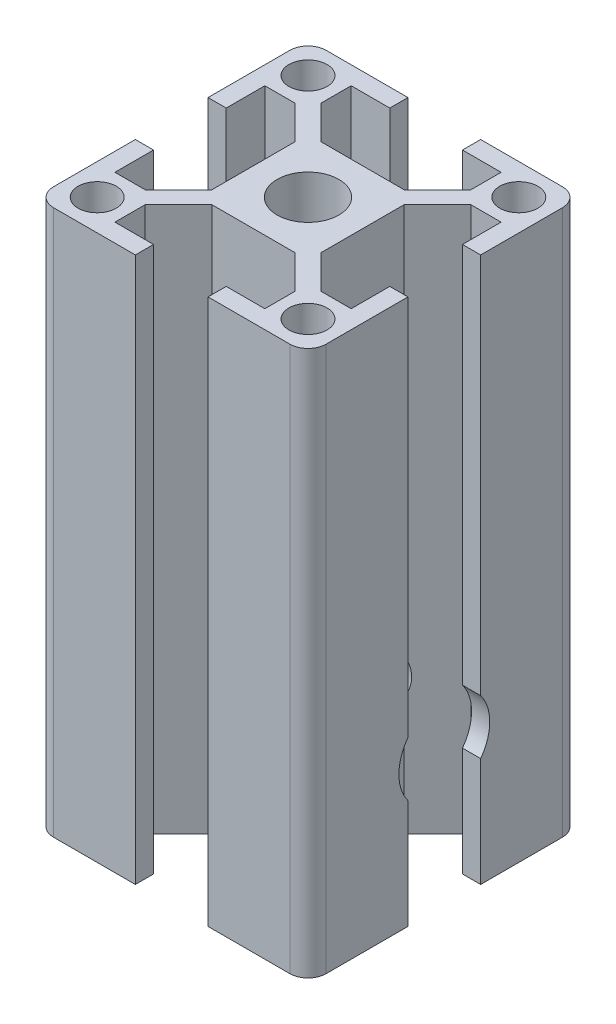
SolidWorks part; units mm, degrees
ref_plane "Front Plane" through (0, 0, 0) normal (0, 0, 1) x (1, 0, 0)
ref_plane "Top Plane" through (0, 0, 0) normal (0, 1, 0) x (1, 0, 0)
ref_plane "Right Plane" through (0, 0, 0) normal (1, 0, 0) x (0, 0, -1)
sketch "Sketch1" plane through (0, 0, 0) normal (0, 1, 0) x (1, 0, 0)
  line L0 (-4, 15) -> (-4, 13)
  line L1 (-13, -15) -> (-4, -15)
  line L2 (-15, -13) -> (-15, -4)
  line L3 (-13, 15) -> (-4, 15)
  line L4 (15, -13) -> (15, -4)
  line L5 (-15, -15) -> (15, 15) construction
  line L6 (-15, 15) -> (15, -15) construction
  line L7 (-4, 13) -> (-8.25, 13)
  line L8 (-8.25, 13) -> (-8.25, 9.6642)
  line L9 (-8.25, 9.6642) -> (-4.5858, 6)
  line L10 (-4.5858, 6) -> (4.5858, 6)
  line L11 (0, 0) -> (0, 50000) construction
  line L12 (0, 0) -> (50000, 0) construction
  line L13 (-6, 4.5858) -> (-6, -4.5858)
  line L14 (-9.6642, 8.25) -> (-6, 4.5858)
  line L15 (-13, 8.25) -> (-9.6642, 8.25)
  line L16 (-13, 4) -> (-13, 8.25)
  line L17 (-15, 4) -> (-13, 4)
  line L18 (4, 15) -> (4, 13)
  line L19 (4, 13) -> (8.25, 13)
  line L20 (8.25, 13) -> (8.25, 9.6642)
  line L21 (8.25, 9.6642) -> (4.5858, 6)
  line L22 (6, 4.5858) -> (6, -4.5858)
  line L23 (9.6642, 8.25) -> (6, 4.5858)
  line L24 (13, 8.25) -> (9.6642, 8.25)
  line L25 (13, 4) -> (13, 8.25)
  line L26 (15, 4) -> (13, 4)
  line L27 (15, -4) -> (13, -4)
  line L28 (13, -4) -> (13, -8.25)
  line L29 (13, -8.25) -> (9.6642, -8.25)
  line L30 (9.6642, -8.25) -> (6, -4.5858)
  line L31 (8.25, -9.6642) -> (4.5858, -6)
  line L32 (8.25, -13) -> (8.25, -9.6642)
  line L33 (4, -13) -> (8.25, -13)
  line L34 (4, -15) -> (4, -13)
  line L35 (-4, -15) -> (-4, -13)
  line L36 (-4, -13) -> (-8.25, -13)
  line L37 (-8.25, -13) -> (-8.25, -9.6642)
  line L38 (-8.25, -9.6642) -> (-4.5858, -6)
  line L39 (-4.5858, -6) -> (4.5858, -6)
  line L40 (-13, -8.25) -> (-9.6642, -8.25)
  line L41 (-9.6642, -8.25) -> (-6, -4.5858)
  line L42 (-13, -4) -> (-13, -8.25)
  line L43 (-15, -4) -> (-13, -4)
  line L44 (4, 15) -> (13, 15)
  line L45 (15, 4) -> (15, 13)
  line L46 (4, -15) -> (13, -15)
  line L47 (-15, 4) -> (-15, 13)
  arc A0 (13, 15) -> (15, 13) centre (13, 13) cw
  arc A1 (13, -15) -> (15, -13) centre (13, -13) ccw
  arc A2 (-13, -15) -> (-15, -13) centre (-13, -13) cw
  arc A3 (-15, 13) -> (-13, 15) centre (-13, 13) cw
  circle A4 centre (-11.6, 11.6) radius 2.1
  circle A5 centre (11.6, 11.6) radius 2.1
  circle A6 centre (11.6, -11.6) radius 2.1
  circle A7 centre (-11.6, -11.6) radius 2.1
  circle A8 centre (0, 0) radius 3.4
  point P0 (0, 0)
  point P41 (0, 6)
  point P56 (6, 0)
  point P69 (-6, 0)
  dimension "D2" = 2
  dimension "D8" = 4.2
  dimension "D10" = 6.8
  dimension "D1" = 30
  dimension "D3" = 8
  dimension "D4" = 16.5
  dimension "D5" = 7
  dimension "D6" = 12
  dimension "D7" = 2
  dimension "D9" = 23.2
extrude "profile length" add sketch "Sketch1" along normal mid plane 60
sketch "shelf attachment holes" plane through (0, 0, 0) normal (0, 0, 1) x (1, 0, 0)
  line L0 (0, -796) -> (0, 49204) construction
  line L1 (-4.5858, -30) -> (4.5858, -30) construction
  circle A0 centre (0, 50) radius 2.5
  point P4 (0, -30)
  dimension "D2" = 5
  dimension "D1" = 80
extrude "shelf attachment holes cut" [suppressed] cut sketch "shelf attachment holes" against normal through all both and the other way through all contours A0
pattern_linear "shelf attachment holes pattern" [suppressed] count 39 spacing 35
sketch "Sketch2" plane through (0, 0, 0) normal (1, 0, 0) x (0, 0, -1)
  line L0 (-3.4, -30) -> (3.4, -30) construction
  line L1 (0, -15) -> (0, -30) construction
  line L2 (-3.4, -30) -> (3.4, -30) construction
  circle A0 centre (0, -15) radius 5
  point P0 (0, -15)
  dimension "D2" = 10
  dimension "D1" = 15
extrude "Cut-Extrude1" cut sketch "Sketch2" against normal through all both and the other way through all
sketch "Sketch3" [suppressed] plane through (0, 0, 0) normal (0, 0, 1) x (1, 0, 0)
  line L0 (0, -741.5) -> (0, -756.5) construction
  line L1 (-4.5858, -756.5) -> (4.5858, -756.5) construction
  line L2 (0, 741.5) -> (0, 756.5) construction
  line L3 (-4.5858, 756.5) -> (4.5858, 756.5) construction
  circle A0 centre (0, -741.5) radius 4
  circle A1 centre (0, 741.5) radius 4
  dimension "D2" = 8
  dimension "D1" = 15
extrude "Cut-Extrude2" [suppressed] cut sketch "Sketch3" against normal through all both and the other way through all
